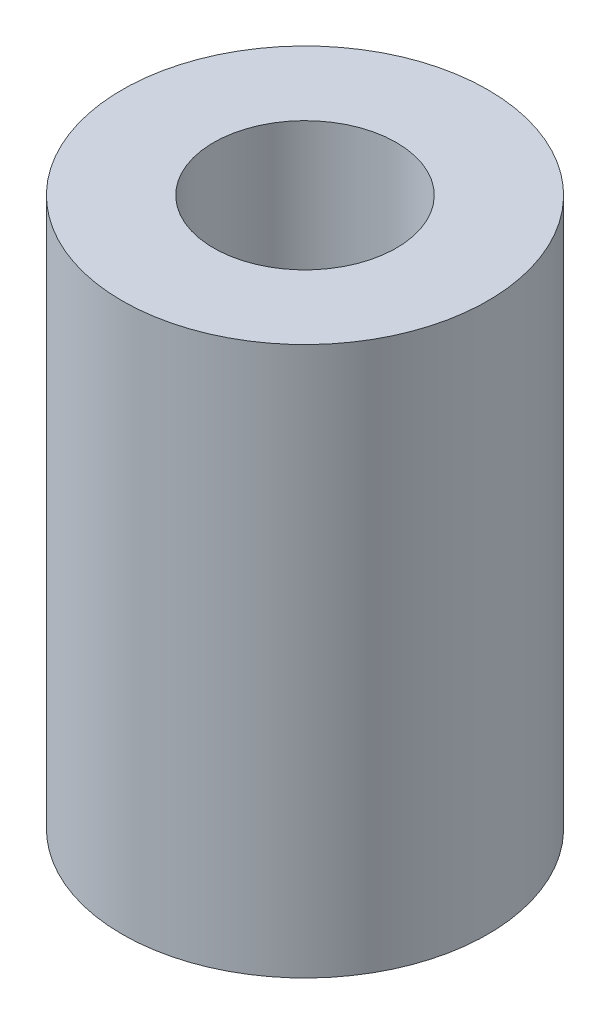
SolidWorks part; units mm, degrees
material "Brass"
ref_plane "Front Plane" through (0, 0, 0) normal (0, 0, 1) x (1, 0, 0)
ref_plane "Top Plane" through (0, 0, 0) normal (0, 1, 0) x (1, 0, 0)
ref_plane "Right Plane" through (0, 0, 0) normal (1, 0, 0) x (0, 0, -1)
sketch "Sketch1" plane through (0, 0, 0) normal (0, 1, 0) x (1, 0, 0)
  circle A0 centre (0, 0) radius 1.5875
  circle A1 centre (0, 0) radius 3.175
  dimension "D1" = 3.175
  dimension "D2" = 6.35
extrude "Boss-Extrude1" add sketch "Sketch1" along normal blind 9.525
